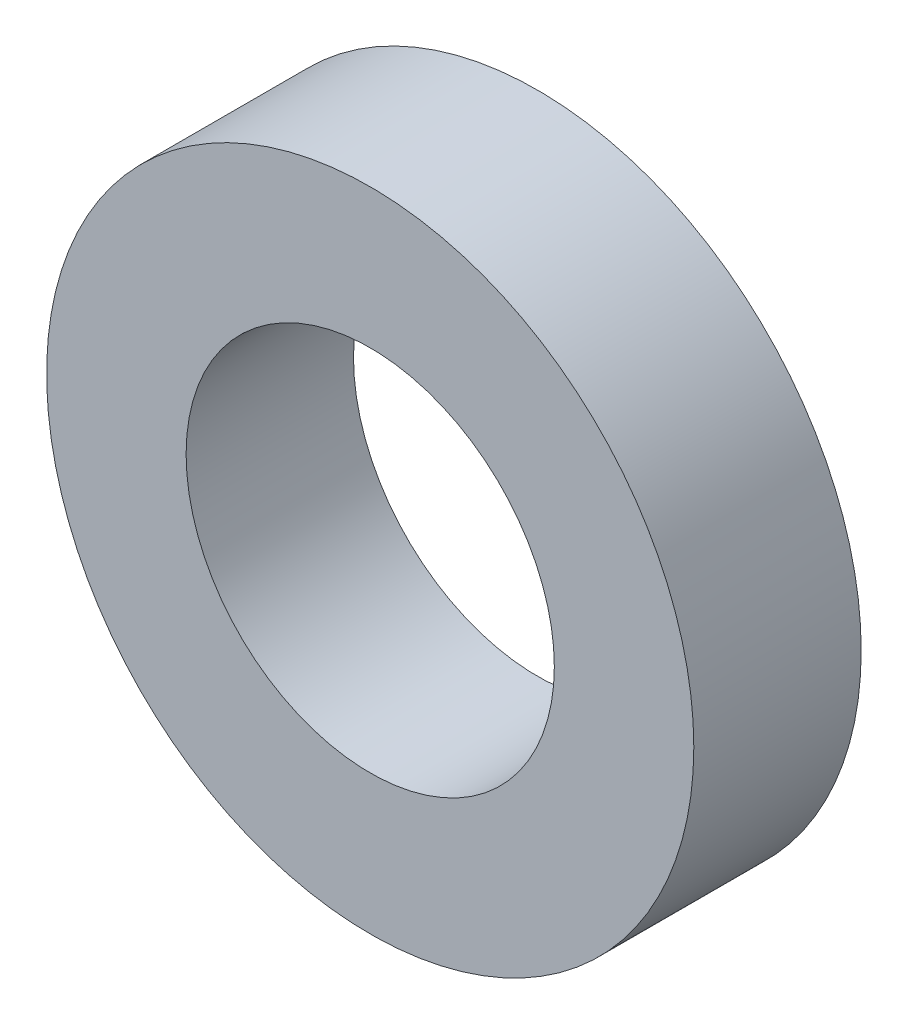
SolidWorks part; units mm, degrees
ref_plane "前视基准面" through (0, 0, 0) normal (0, 0, 1) x (1, 0, 0)
ref_plane "上视基准面" through (0, 0, 0) normal (0, 1, 0) x (1, 0, 0)
ref_plane "右视基准面" through (0, 0, 0) normal (1, 0, 0) x (0, 0, -1)
other "Configuration Table"
sketch "草图1" plane through (0, 0, 0) normal (0, 0, 1) x (1, 0, 0)
  circle A2 centre (0, 0) radius 2.9
  circle A3 centre (0, 0) radius 1.65
extrude "M3安装垫片_D3p3_厚1p5" add sketch "草图1" along normal blind 1.5
